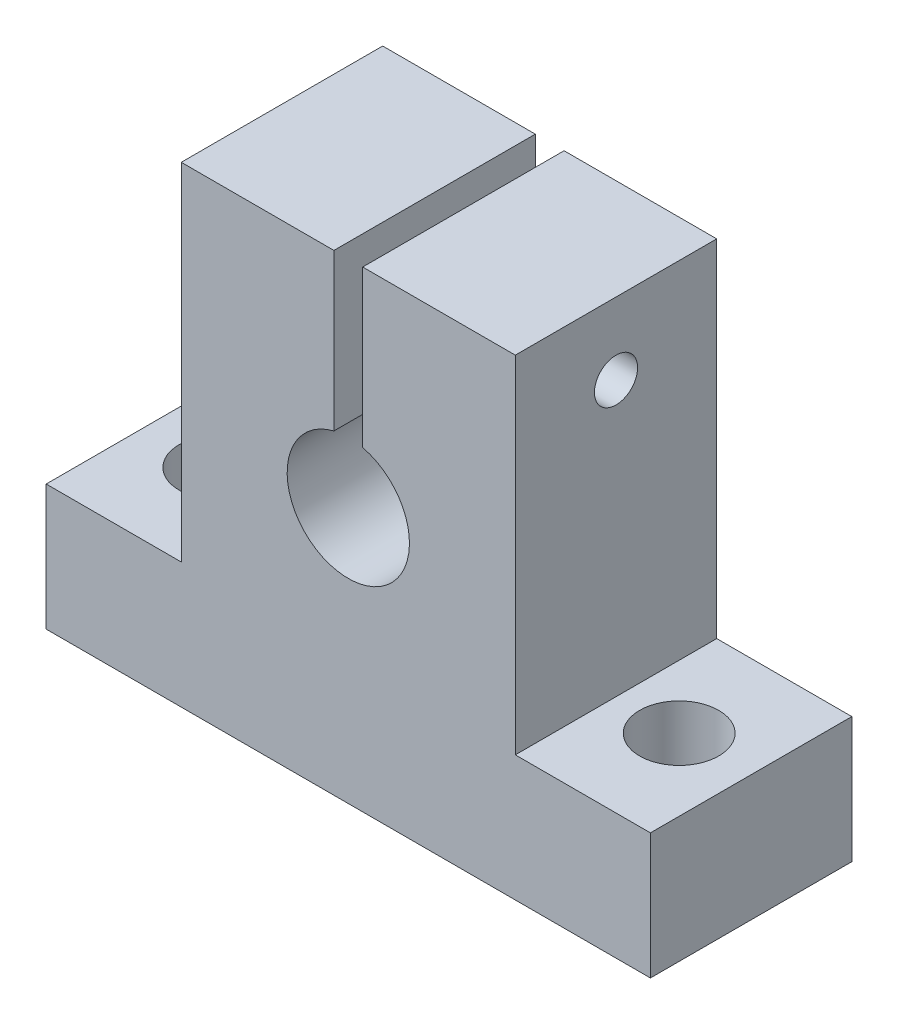
SolidWorks part; units mm, degrees
material "AISI 304"
ref_plane "Front Plane" through (0, 0, 0) normal (0, 0, 1) x (1, 0, 0)
ref_plane "Top Plane" through (0, 0, 0) normal (0, 1, 0) x (1, 0, 0)
ref_plane "Right Plane" through (0, 0, 0) normal (1, 0, 0) x (0, 0, -1)
sketch "Sketch1" plane through (0, 0, 0) normal (0, 0, 1) x (1, 0, 0)
  line L0 (0, 0) -> (42, 0)
  line L1 (42, 0) -> (42, 8.7375)
  line L2 (42, 8.7375) -> (32.6093, 8.7375)
  line L3 (32.6093, 8.7375) -> (32.6093, 32.8)
  line L4 (9.3907, 32.8) -> (20, 32.8)
  line L5 (9.3907, 32.8) -> (9.3907, 8.7375)
  line L6 (9.3907, 8.7375) -> (0, 8.7375)
  line L7 (0, 8.7375) -> (0, 0)
  line L8 (20, 32.8) -> (20, 17.8)
  line L9 (20, 17.8) -> (22, 17.8)
  line L10 (22, 17.8) -> (22, 32.8)
  line L11 (22, 32.8) -> (32.6093, 32.8)
  dimension "D1" = 42
  dimension "D2" = 32.8
  dimension "D3" = 2
  dimension "D4" = 15
extrude "Boss-Extrude1" add sketch "Sketch1" along normal blind 14
sketch "Sketch2" plane through (0, 0, 14) normal (0, 0, 1) x (1, 0, 0)
  line L0 (22, 17.8) -> (20, 17.8) construction
  circle A0 centre (21, 17.8) radius 4.25
  dimension "D1" = 8.5
extrude "Cut-Extrude1" cut sketch "Sketch2" against normal through all
sketch "Sketch3" plane through (0, 8.7375, 0) normal (0, 1, 0) x (1, 0, 0)
  line L0 (5, -7) -> (37, -7) construction
  line L5 (9.3907, 0) -> (0, 0) construction
  line L6 (0, -14) -> (0, 0) construction
  circle A0 centre (5, -7) radius 2.75
  circle A1 centre (37, -7) radius 2.75
  dimension "D1" = 5.5
  dimension "D2" = 32
  dimension "D3" = 7
  dimension "D4" = 5
extrude "Cut-Extrude2" cut sketch "Sketch3" against normal through all
sketch "Sketch4" plane through (32.6093, 0, 0) normal (1, 0, 0) x (0, 0, -1)
  line L0 (-14, 32.8) -> (0, 32.8) construction
  line L1 (0, 8.7375) -> (0, 32.8) construction
  circle A0 centre (-7, 27.8) radius 1.5
  dimension "D1" = 3
  dimension "D3" = 7
  dimension "D2" = 5
extrude "Cut-Extrude3" cut sketch "Sketch4" against normal through all
